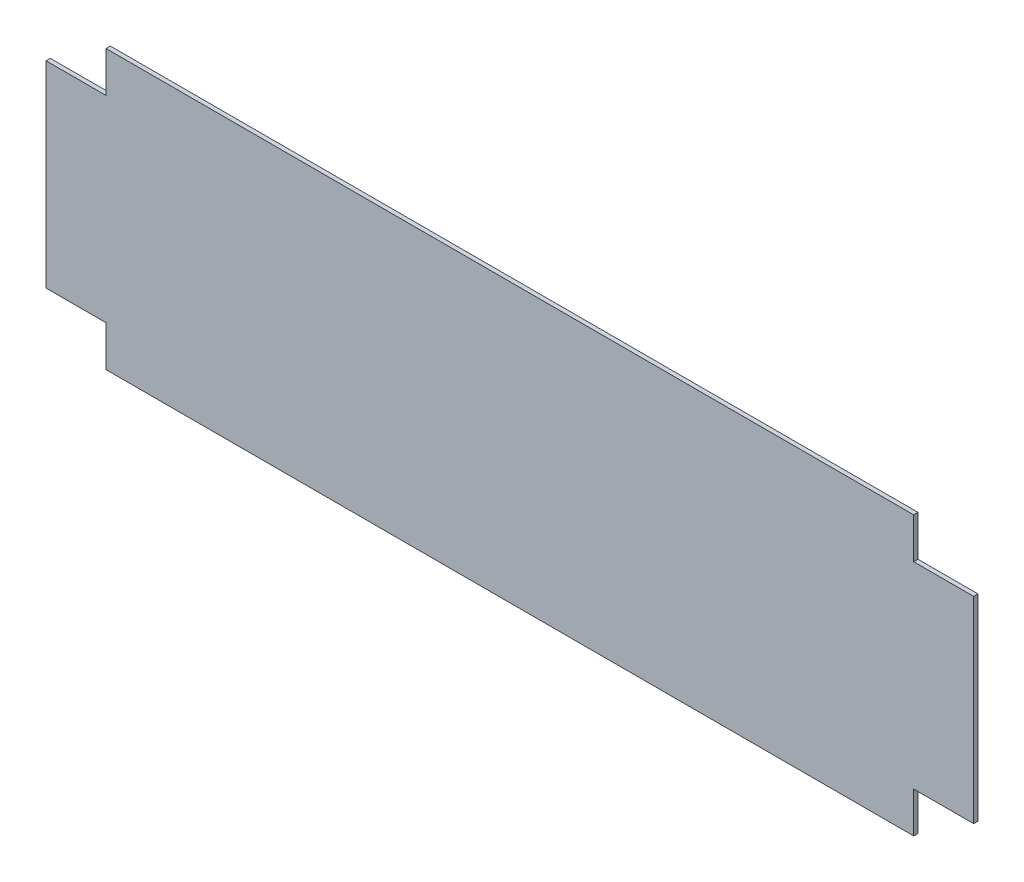
SolidWorks part; units mm, degrees
ref_plane "Front Plane" through (0, 0, 0) normal (0, 0, 1) x (1, 0, 0)
ref_plane "Top Plane" through (0, 0, 0) normal (0, 1, 0) x (1, 0, 0)
ref_plane "Right Plane" through (0, 0, 0) normal (1, 0, 0) x (0, 0, -1)
sketch "Sketch1" plane through (0, 0, 0) normal (0, 0, 1) x (1, 0, 0)
  line L0 (-11.525, 92.0974) -> (16.5521, 92.0974)
  line L5 (394.3979, 92.0974) -> (422.475, 92.0974)
  line L6 (422.475, 92.0974) -> (422.475, 0)
  line L7 (422.475, 0) -> (394.3979, 0)
  line L11 (16.5521, 0) -> (-11.525, 0)
  line L12 (-11.525, 0) -> (-11.525, 92.0974)
  line L15 (16.5521, 92.0974) -> (16.5521, 111.101)
  line L16 (16.5521, 111.101) -> (394.3979, 111.101)
  line L17 (394.3979, 111.101) -> (394.3979, 92.0974)
  line L18 (16.5521, 0) -> (16.5521, -19.0036)
  line L19 (16.5521, -19.0036) -> (394.3979, -19.0036)
  line L20 (394.3979, -19.0036) -> (394.3979, 0)
extrude "Boss-Extrude1" add sketch "Sketch1" along normal blind 2
